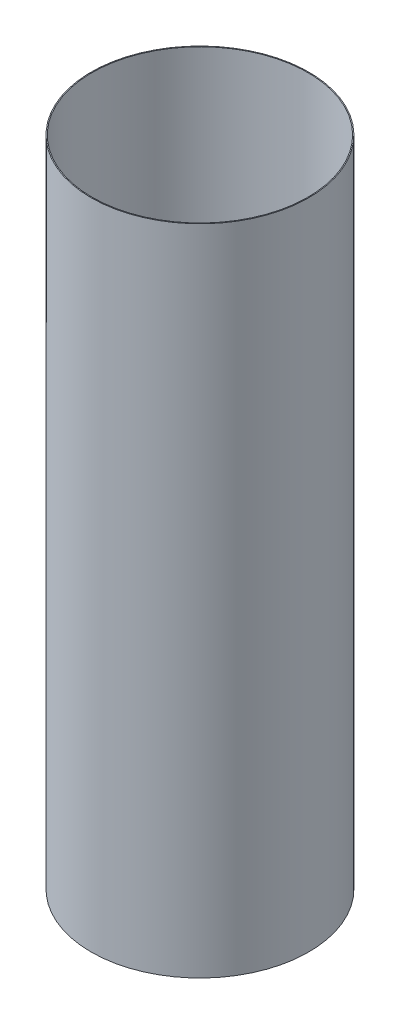
SolidWorks part; units mm, degrees
ref_plane "Front Plane" through (0, 0, 0) normal (0, 0, 1) x (1, 0, 0)
ref_plane "Top Plane" through (0, 0, 0) normal (0, 1, 0) x (1, 0, 0)
ref_plane "Right Plane" through (0, 0, 0) normal (1, 0, 0) x (0, 0, -1)
sketch "Sketch2" plane through (0, 0, 0) normal (0, 1, 0) x (1, 0, 0)
  circle A0 centre (0, 0) radius 75.565
  circle A1 centre (0, 0) radius 76.2
  dimension "D1" = 152.4
  dimension "D2" = 151.13
extrude "Boss-Extrude1" add sketch "Sketch2" along normal blind 457.2
